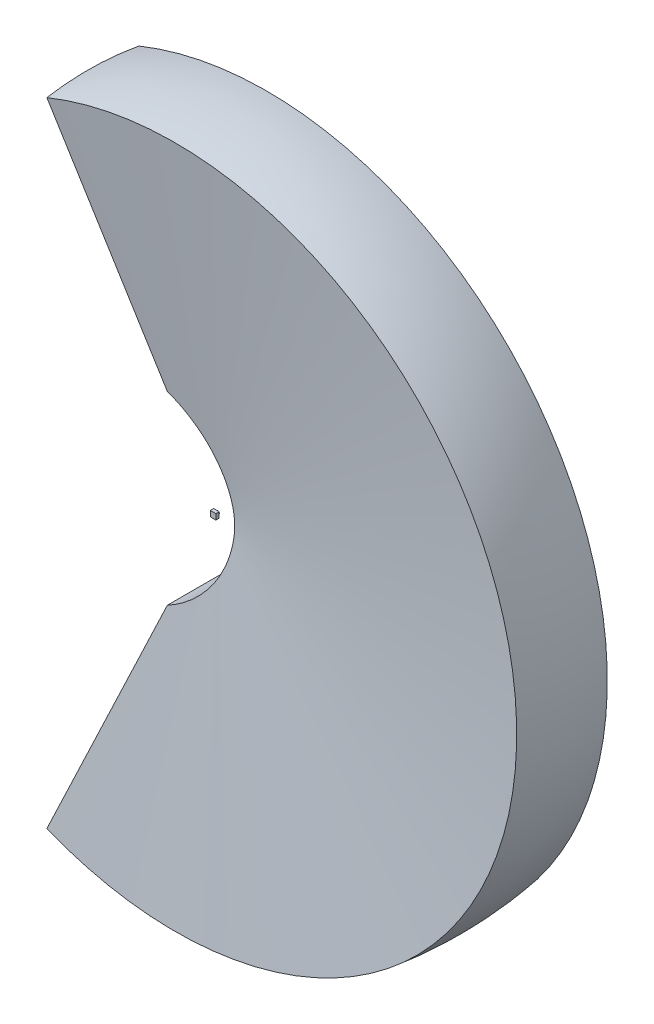
SolidWorks part; units mm, degrees
material "Acciaio al carbonio semplice"
ref_plane "Piano frontale" through (0, 0, 0) normal (0, 0, 1) x (1, 0, 0)
ref_plane "Piano superiore" through (0, 0, 0) normal (0, 1, 0) x (1, 0, 0)
ref_plane "Piano destro" through (0, 0, 0) normal (1, 0, 0) x (0, 0, -1)
sketch "Schizzo1" plane through (0, 0, 0) normal (0, 0, 1) x (1, 0, 0)
  line L1 (-32.5, 32.5) -> (32.5, 32.5)
  line L2 (-32.5, 32.5) -> (-32.5, -32.5)
  line L3 (-32.5, -32.5) -> (32.5, -32.5)
  line L4 (32.5, 32.5) -> (32.5, -32.5)
  line L5 (-32.5, 32.5) -> (32.5, -32.5) construction
  line L6 (-32.5, -32.5) -> (32.5, 32.5) construction
  point P0 (0, 0)
  dimension "D1" = 65
extrude "Estrusione-Estrusione1" add sketch "Schizzo1" along normal blind 39.5
ref_plane "Piano1" through (0, 0, -60.5) normal (0, 0, -1) x (-1, 0, 0)
ref_plane "Piano2" through (0, 0, -585.3) normal (0, 0, -1) x (-1, 0, 0)
ref_plane "Piano3" through (-202.66, 0, 0) normal (-1, 0, 0) x (0, 0, 1)
ref_plane "Piano4" through (0, -500, 0) normal (0, -1, 0) x (-1, 0, 0)
ref_plane "Piano7" through (0, 0, 139.5) normal (0, 0, 1) x (1, 0, 0)
ref_plane "Piano5" through (32.5, 0, 0) normal (1, 0, 0) x (0, 0, -1)
sketch "Schizzo2" plane through (0, 0, 0) normal (0, 1, 0) x (1, 0, 0)
  line L0 (0, 0) -> (0, 20.5)
  line L1 (0, 20.5) -> (12.48, 20.5)
  line L2 (0, 0) -> (24, 0)
  line L3 (32.5, 0) -> (-32.5, 0) construction
  line L5 (32.5, -39.5) -> (-32.5, -39.5) construction
  arc A0 (24, 0) -> (12.48, 20.5) centre (0, 0) ccw
  dimension "D1" = 60
  dimension "D2" = 24
revolve "Rivoluzione1" add sketch "Schizzo2" angle 360 about L0
sketch "Schizzo4" plane through (0, 0, 0) normal (0, 1, 0) x (1, 0, 0)
  line L0 (32.5, -39.5) -> (-32.5, -39.5) construction
  line L1 (0, -992.5) -> (0, 49007.5) construction
  point P0 (0, 7.5)
  dimension "D1" = 47
sketch "Schizzo13" plane through (0, 0, 0) normal (0, 1, 0) x (1, 0, 0)
  line L0 (0, 7.5) -> (451.4268, 585.3) construction
  line L1 (32.5, 0) -> (-32.5, 0) construction
  line L2 (35.75, 585.3) -> (-35.75, 585.3) construction
  dimension "D1" = 52
ref_point "Punto1"
sketch "Schizzo5" plane through (0, 0, 0) normal (0, 1, 0) x (1, 0, 0)
  line L2 (-999.5584, 7.5) -> (49000.4416, 7.5) construction
  line L3 (0, -992.5) -> (0, 49007.5) construction
  line L4 (20.1593, 33.3027) -> (2462.6459, 3159.543) construction
  line L5 (0, 7.5) -> (2462.6459, 3159.543) construction
  line L7 (0, 7.5) -> (3970.1846, -479.9774) construction
  line L8 (32.5, 3.5095) -> (3970.1846, -479.9774)
  line L11 (20.1593, 33.3027) -> (451.4268, 585.3)
  line L12 (451.4268, 585.3) -> (3958.0484, 585.3)
  line L13 (35.75, 585.3) -> (-35.75, 585.3) construction
  arc A0 (3970.1846, -479.9774) -> (2462.6459, 3159.543) centre (0, 7.5) ccw construction
  arc A1 (32.5, 3.5095) -> (20.1593, 33.3027) centre (0, 7.5) ccw
  arc A2 (3970.1846, -479.9774) -> (3958.0484, 585.3) centre (0, 7.5) ccw
  point P11 (4000, 7.5)
  dimension "D1" = 52
  dimension "D2" = 4000
  dimension "D4" = 7
revolve "Rivoluzione5" add sketch "Schizzo5" angle 360 about L3
sketch "Schizzo8" plane through (32.5, 0, 0) normal (1, 0, 0) x (0, 0, -1)
  line L0 (585.3, -35.75) -> (585.3, 35.75) construction
  line L1 (-814.7, 500) -> (-39.5, 500)
  line L2 (-814.7, 500) -> (-814.7, -500)
  line L3 (-814.7, -500) -> (-39.5, -500)
  line L4 (585.3, 500) -> (585.3, -500)
  line L5 (-814.7, 500) -> (585.3, -500) construction
  line L6 (-814.7, -500) -> (585.3, 500) construction
  line L9 (-39.5, -500) -> (-39.5, 500)
  line L10 (-39.5, -32.5) -> (-39.5, 32.5) construction
  line L11 (60.5, 500) -> (60.5, -500)
  line L12 (60.5, -35.75) -> (60.5, 35.75) construction
  line L13 (60.5, -500) -> (585.3, -500)
  line L14 (60.5, 500) -> (585.3, 500)
  point P0 (-114.7, 0)
  point P10 (-39.5, 0)
  point P21 (60.5, 0)
  dimension "D1" = 1400
  dimension "D2" = 1000
extrude "Taglio-Estrusione4" cut sketch "Schizzo8" along direction (1, 0, 0) on the side against the normal up to next
sketch3d "Schizzo3D1"
  line L0 (0, 0, -7.5) -> (-181.9851, -500, -7.5) construction
  line L1 (-181.9851, -500, -7.5) -> (0, -500, -7.5) construction
  line L2 (0, -500, -7.5) -> (0, 0, -7.5) construction
  line L3 (-32.5, 32.5, 39.5) -> (-32.5, -32.5, 39.5) construction
  line L4 (-32.5, -32.5, 39.5) -> (32.5, -32.5, 39.5) construction
  line L5 (0, 0, -7.5) -> (0, 0, -60.5) construction
  line L6 (0, 0, 992.5) -> (0, 0, -49007.5) construction
  line L10 (32.5, 0, -60.5) -> (0, 0, -7.5) construction
  line L13 (32.5, -500, -60.5) -> (32.5, 0, -60.5) construction
  line L14 (0, 0, -60.5) -> (32.5, -500, -60.5)
  line L22 (32.5, -500, -60.5) -> (0, 0, -7.5) construction
  line L23 (0, 0, -60.5) -> (32.5, 0, -60.5)
  line L24 (32.5, -500, -60.5) -> (32.5, 0, -60.5)
  dimension "D1" = 20
  dimension "D2" = 500
sketch "Schizzo11" plane through (0, 0, 0) normal (0, 1, 0) x (1, 0, 0)
  line L0 (35.75, 585.3) -> (-35.75, 585.3) construction
  line L1 (0, -514.7) -> (-40000, -514.7)
  line L2 (0, -514.7) -> (0, -39.5)
  line L3 (0, 585.3) -> (-40000, 585.3)
  line L4 (-40000, -514.7) -> (-40000, 585.3)
  line L9 (0, 60.5) -> (-202.66, 60.5)
  line L11 (-202.66, -39.5) -> (-202.66, 60.5)
  line L12 (32.5, -39.5) -> (-32.5, -39.5) construction
  line L13 (0, -39.5) -> (-202.66, -39.5)
  line L14 (0, 60.5) -> (0, 585.3)
  line L16 (-202.66, 21.725) -> (-202.66, -21.725) construction
  line L17 (35.75, 60.5) -> (-35.75, 60.5) construction
  dimension "D1" = 40000
  dimension "D2" = 1100
revolve "Taglia-Rivoluzione1" cut sketch "Schizzo11" angle 135.87 mid plane about L1
sketch "Schizzo12" plane through (32.5, 0, 0) normal (1, 0, 0) x (0, 0, -1)
  line L0 (7.5, 0) -> (60.5, -500) construction
  line L2 (0, -32.5) -> (0, 32.5) construction
  line L3 (60.5, -500) -> (585.3, -5450.9434)
  line L4 (585.3, -5450.9434) -> (585.3, 5450.9422)
  line L6 (585.3, -35.75) -> (585.3, 35.75) construction
  line L7 (60.5, -500) -> (60.5, 499.9988)
  line L11 (60.5, 499.9988) -> (585.3, 5450.9422)
  dimension "D1" = 502.8012
  dimension "D2" = 6.051
  dimension "D3" = 6.051
  dimension "D4" = 502.8
extrude "Taglio-Estrusione8" [suppressed] cut sketch "Schizzo12" against normal up to next
sketch "Schizzo15" plane through (0, 0, 0) normal (1, 0, 0) x (0, 0, -1)
  line L0 (60.5, 0) -> (585.3, 0)
  line L1 (-200992.5, 0) -> (249007.5, 0) construction
  line L2 (585.3, 0) -> (585.3, -4000)
  line L4 (60.5, -35.75) -> (60.5, 35.75) construction
  line L5 (585.3, -35.75) -> (585.3, 35.75) construction
  line L6 (7.5, 0) -> (60.2315, -500.0272) construction
  line L9 (60.2315, -500.0272) -> (585.3, -4000)
  line L11 (0, -32.5) -> (0, 32.5) construction
  line L12 (60.5, 0) -> (60.2315, -500.0272)
  dimension "D1" = 6.02
  dimension "D2" = 502.8
  dimension "D3" = 4000
revolve "Taglia-Rivoluzione3" [suppressed] cut sketch "Schizzo15" angle 3.72 about L1
sketch "Schizzo16" plane through (0, 0, -585.3) normal (0, 0, -1) x (-1, 0, 0)
  circle A0 centre (967.5, 0) radius 1200
  dimension "D1" = 2400
  dimension "D2" = 967.5
extrude "Taglio-Estrusione11" cut sketch "Schizzo16" against normal up to next
mirror "Specchia2" [suppressed] about plane through (0, 0, 0) normal (0, 1, 0)
